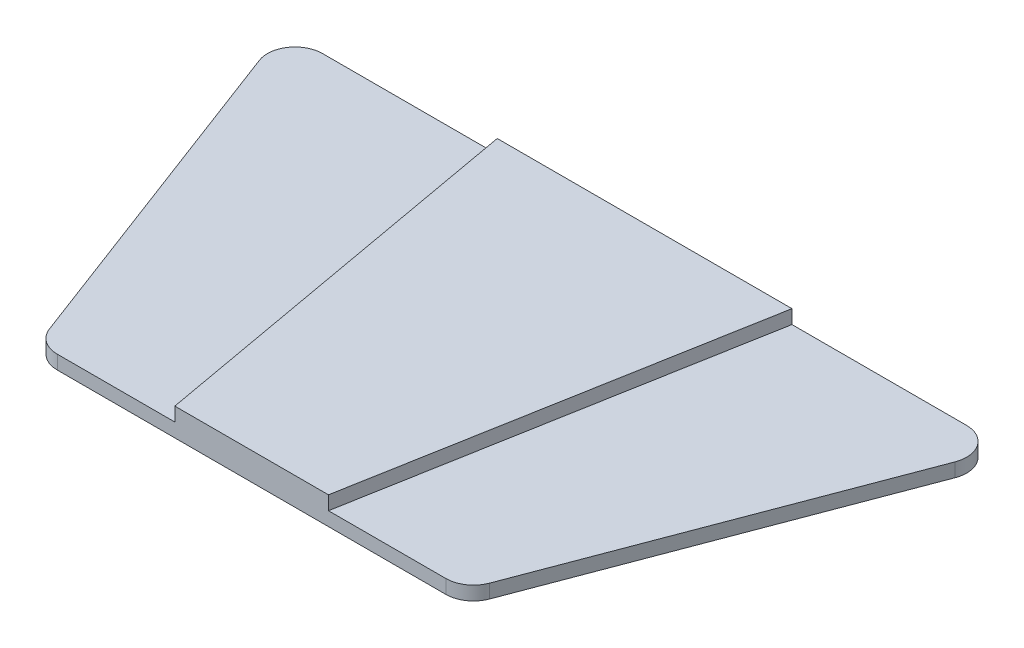
SolidWorks part; units mm, degrees
ref_plane "Front Plane" through (0, 0, 0) normal (0, 0, 1) x (1, 0, 0)
ref_plane "Top Plane" through (0, 0, 0) normal (0, 1, 0) x (1, 0, 0)
ref_plane "Right Plane" through (0, 0, 0) normal (1, 0, 0) x (0, 0, -1)
sketch "Sketch1" plane through (0, 0, 0) normal (0, 1, 0) x (1, 0, 0)
  line L0 (-53.4083, 37.7559) -> (53.4083, 37.7559)
  line L1 (57.6847, 31.5668) -> (36.4976, -24.4614)
  line L2 (-32.2212, -27.4163) -> (32.2212, -27.4163)
  line L3 (0, 0) -> (0, 52.3797) construction
  line L5 (-57.6847, 31.5668) -> (-36.4976, -24.4614)
  arc A0 (57.6847, 31.5668) -> (53.4083, 37.7559) centre (53.4083, 33.1839) ccw
  arc A1 (36.4976, -24.4614) -> (32.2212, -27.4163) centre (32.2212, -22.8443) cw
  arc A2 (-36.4976, -24.4614) -> (-32.2212, -27.4163) centre (-32.2212, -22.8443) ccw
  arc A3 (-57.6847, 31.5668) -> (-53.4083, 37.7559) centre (-53.4083, 33.1839) cw
  point P18 (0, 37.7559)
  dimension "D1" = 4.572
  dimension "D2" = 4.572
extrude "Extrude1" add sketch "Sketch1" against normal blind 2.286
sketch "Sketch2" plane through (0, 0, 0) normal (0, 1, 0) x (1, 0, 0)
  line L0 (-12.7394, -27.4163) -> (12.7394, -27.4163)
  line L1 (-32.2212, -27.4163) -> (32.2212, -27.4163) construction
  line L2 (12.7394, -27.4163) -> (24.4389, 37.7559)
  line L3 (53.4083, 37.7559) -> (-53.4083, 37.7559) construction
  line L4 (24.4389, 37.7559) -> (-24.4389, 37.7559)
  line L6 (-12.7394, -27.4163) -> (-24.4389, 37.7559)
extrude "Extrude2" add sketch "Sketch2" along normal blind 2.286
sketch "Sketch3" plane through (0, 0, 0) normal (0, 1, 0) x (1, 0, 0)
  ellipse E0 centre (0, 6.3398) end of major axis (32.2385, 6.3398) minor radius 23.0089
